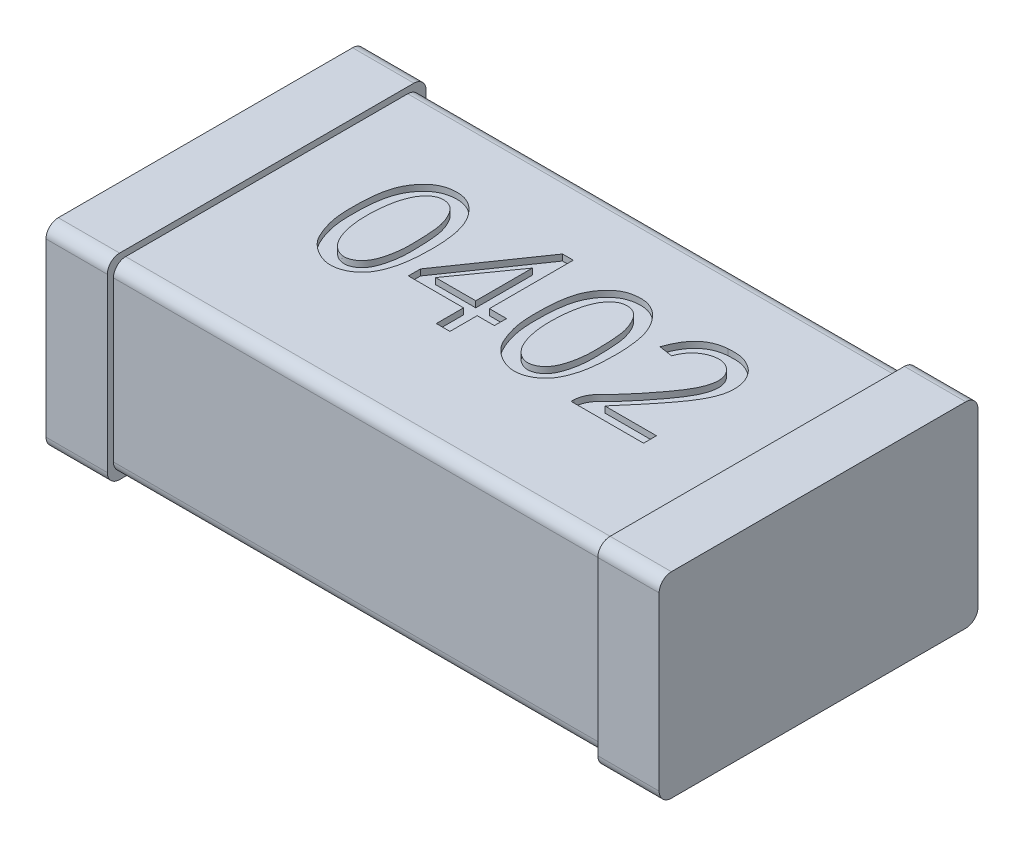
SolidWorks part; units mm, degrees
ref_plane "前视基准面" through (0, 0, 0) normal (0, 0, 1) x (1, 0, 0)
ref_plane "上视基准面" through (0, 0, 0) normal (0, 1, 0) x (1, 0, 0)
ref_plane "右视基准面" through (0, 0, 0) normal (1, 0, 0) x (0, 0, -1)
sketch "草图1" plane through (0, 0, 0) normal (0, 1, 0) x (1, 0, 0)
  line L0 (-31.3913, 0) -> (27.0565, 0) construction
  line L1 (0, 12.4242) -> (0, -8.2436) construction
  line L3 (-0.5, -0.25) -> (0.5, -0.25)
  line L4 (-0.5, -0.25) -> (-0.5, 0.25)
  line L5 (-0.5, 0.25) -> (0.5, 0.25)
  line L6 (0.5, -0.25) -> (0.5, 0.25)
  dimension "D1" = 1
  dimension "D2" = 0.5
extrude "凸台-拉伸1" add sketch "草图1" along normal blind 0.3
sketch "草图2" plane through (-0.5, 0, 0) normal (-1, 0, 0) x (0, 0, 1)
  line L0 (-0.2947, 0.15) -> (0.2931, 0.15) construction
  line L1 (-0.26, 0.31) -> (0.26, 0.31)
  line L2 (-0.26, 0.31) -> (-0.26, -0.01)
  line L3 (-0.26, -0.01) -> (0.26, -0.01)
  line L4 (0.26, 0.31) -> (0.26, -0.01)
  line L5 (0, -0.0313) -> (0, 0.3371) construction
  line L6 (-0.25, 0.3) -> (0.25, 0.3) construction
  dimension "D1" = 0.32
  dimension "D2" = 0.52
  dimension "D3" = 0.01
extrude "凸台-拉伸2" add sketch "草图2" against normal blind 0.1
sketch "草图3" plane through (0.5, 0, 0) normal (1, 0, 0) x (0, 0, -1)
  line L0 (-0.26, 0.31) -> (0.26, 0.31) construction
  line L1 (-0.26, -0.01) -> (-0.26, 0.31) construction
  line L2 (0.26, -0.01) -> (-0.26, -0.01) construction
  line L3 (0.26, 0.31) -> (0.26, -0.01) construction
  line L4 (-0.26, 0.31) -> (0.26, 0.31)
  line L5 (-0.26, -0.01) -> (-0.26, 0.31)
  line L6 (0.26, -0.01) -> (-0.26, -0.01)
  line L7 (0.26, 0.31) -> (0.26, -0.01)
extrude "凸台-拉伸3" add sketch "草图3" against normal blind 0.1
sketch "草图4" plane through (0, 0.3, 0) normal (0, 1, 0) x (1, 0, 0)
  text T0 "0402" font "黑体" height 0.2
extrude "切除-拉伸1" cut sketch "草图4" against normal blind 0.01
fillet "圆角1" radius 0.02 4 edges at (0, 0, 0.25) (0, 0, -0.25) (0, 0.3, -0.25) (0, 0.3, 0.25)
fillet "圆角2" radius 0.02 8 edges at (0.45, -0.01, -0.26) (-0.45, -0.01, -0.26) (-0.45, -0.01, 0.26) (0.45, -0.01, 0.26) (-0.45, 0.31, 0.26) (0.45, 0.31, 0.26) (0.45, 0.31, -0.26) (-0.45, 0.31, -0.26)
